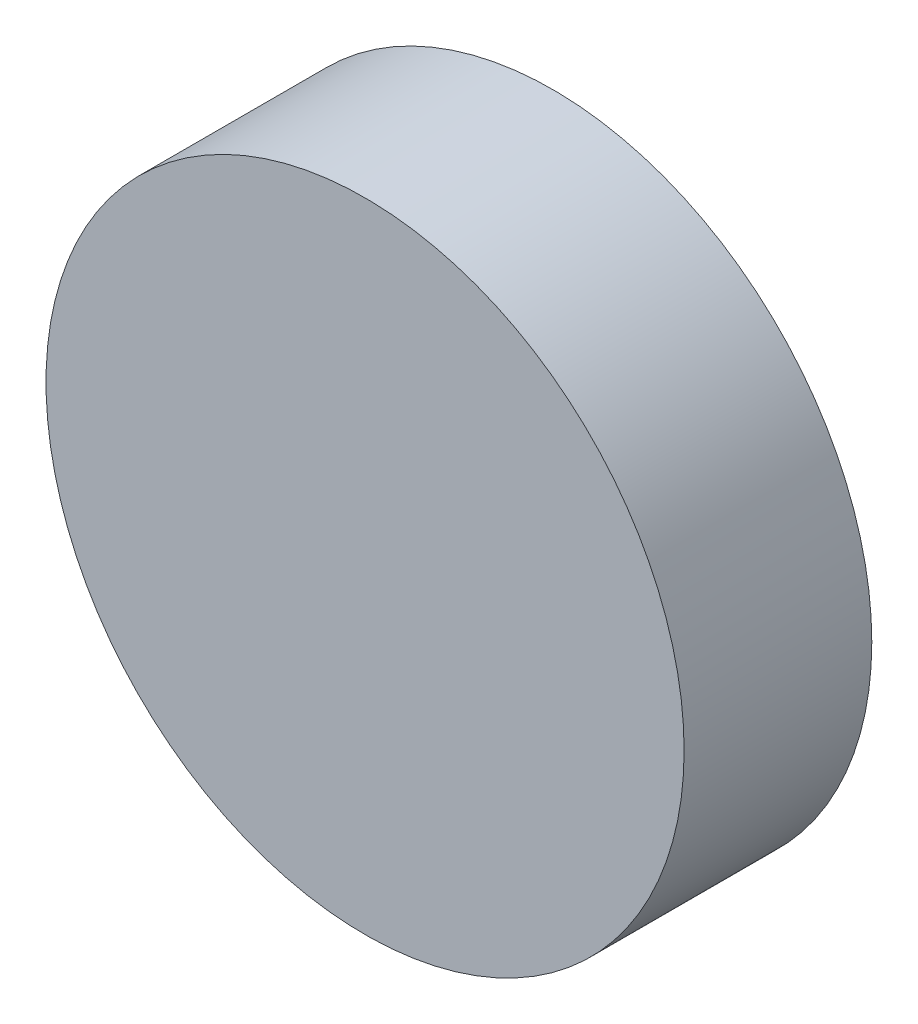
SolidWorks part; units mm, degrees
ref_plane "Front Plane" through (0, 0, 0) normal (0, 0, 1) x (1, 0, 0)
ref_plane "Top Plane" through (0, 0, 0) normal (0, 1, 0) x (1, 0, 0)
ref_plane "Right Plane" through (0, 0, 0) normal (1, 0, 0) x (0, 0, -1)
sketch "Sketch1" plane through (0, 0, 0) normal (0, 0, 1) x (1, 0, 0)
  circle A0 centre (0, 0) radius 8.5
  dimension "D1" = 17
extrude "Boss-Extrude1" add sketch "Sketch1" along normal blind 5
